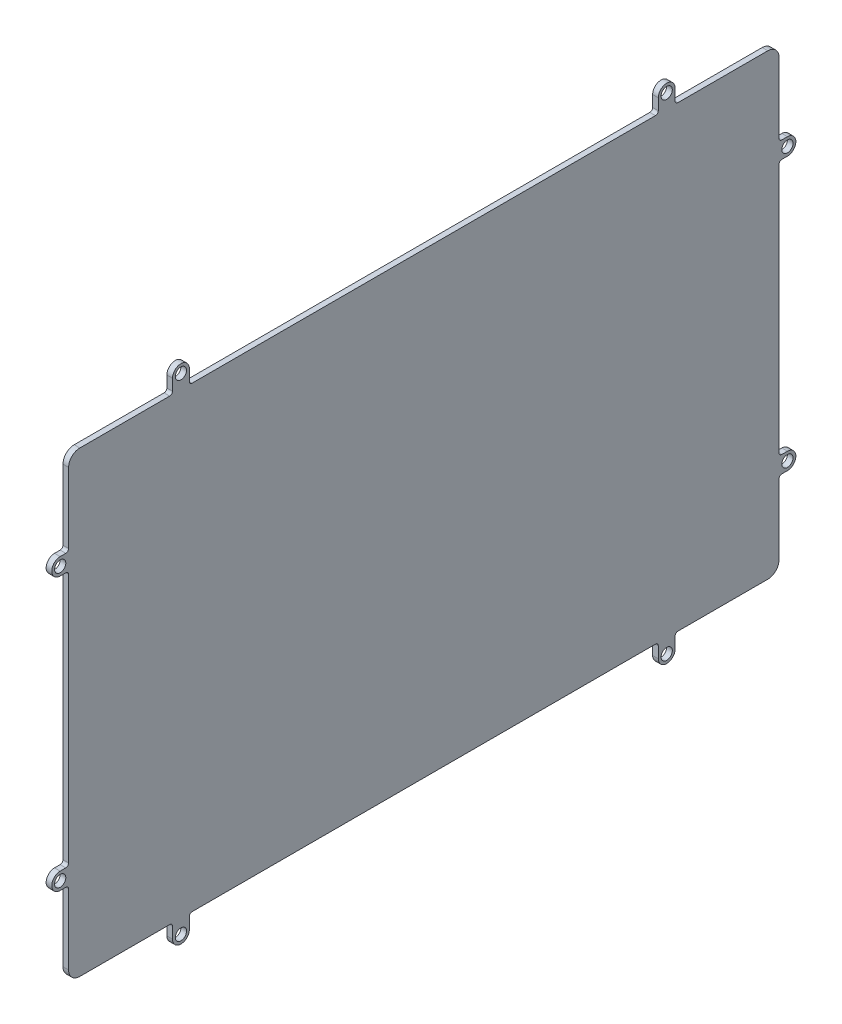
SolidWorks part; units mm, degrees
ref_plane "Ön Düzlem" through (0, 0, 0) normal (1, 0, 0) x (0, 1, 0)
ref_plane "Üst Düzlem" through (0, 0, 0) normal (0, 0, 1) x (0, 1, 0)
ref_plane "Sağ Düzlem" through (0, 0, 0) normal (0, 1, 0) x (-1, 0, 0)
sketch "Çizim1" plane through (0, 0, 0) normal (1, 0, 0) x (0, 1, 0)
  line L0 (78.6986, 126.3502) -> (53.6986, 126.3502)
  line L1 (52.6986, 127.3502) -> (52.6986, 129.3502)
  line L2 (46.6986, 129.3502) -> (46.6986, 127.3502)
  line L3 (45.6986, 126.3502) -> (-43.3014, 126.3502)
  line L4 (-44.3014, 127.3502) -> (-44.3014, 129.3502)
  line L5 (-50.3014, 129.3502) -> (-50.3014, 127.3502)
  line L6 (-51.3014, 126.3502) -> (-76.3014, 126.3502)
  line L7 (-80.3014, 122.3502) -> (-80.3014, 90.3502)
  line L8 (-81.3014, 89.3502) -> (-85.3014, 89.3502)
  line L9 (-85.3014, 83.3502) -> (-81.3014, 83.3502)
  line L10 (-80.3014, 82.3502) -> (-80.3014, -82.6498)
  line L11 (-81.3014, -83.6498) -> (-85.3014, -83.6498)
  line L12 (-85.3014, -89.6498) -> (-81.3014, -89.6498)
  line L13 (-80.3014, -90.6498) -> (-80.3014, -122.6498)
  line L14 (-76.3014, -126.6498) -> (-51.3014, -126.6498)
  line L15 (-50.3014, -127.6498) -> (-50.3014, -129.6498)
  line L16 (-44.3014, -129.6498) -> (-44.3014, -127.6498)
  line L17 (-43.3014, -126.6498) -> (45.6986, -126.6498)
  line L18 (46.6986, -127.6498) -> (46.6986, -129.6498)
  line L19 (52.6986, -129.6498) -> (52.6986, -127.6498)
  line L20 (53.6986, -126.6498) -> (78.6986, -126.6498)
  line L21 (82.6986, -122.6498) -> (82.6986, -90.6498)
  line L22 (83.6986, -89.6498) -> (87.6986, -89.6498)
  line L23 (87.6986, -83.6498) -> (83.6986, -83.6498)
  line L24 (82.6986, -82.6498) -> (82.6986, 82.3502)
  line L25 (83.6986, 83.3502) -> (87.6986, 83.3502)
  line L26 (87.6986, 89.3502) -> (83.6986, 89.3502)
  line L27 (82.6986, 90.3502) -> (82.6986, 122.3502)
  arc A0 (82.6986, 122.3502) -> (78.6986, 126.3502) centre (78.6986, 122.3502) ccw
  arc A1 (52.6986, 127.3502) -> (53.6986, 126.3502) centre (53.6986, 127.3502) ccw
  arc A2 (52.6986, 129.3502) -> (46.6986, 129.3502) centre (49.6986, 129.3502) ccw
  arc A3 (45.6986, 126.3502) -> (46.6986, 127.3502) centre (45.6986, 127.3502) ccw
  arc A4 (-44.3014, 127.3502) -> (-43.3014, 126.3502) centre (-43.3014, 127.3502) ccw
  arc A5 (-44.3014, 129.3502) -> (-50.3014, 129.3502) centre (-47.3014, 129.3502) ccw
  arc A6 (-51.3014, 126.3502) -> (-50.3014, 127.3502) centre (-51.3014, 127.3502) ccw
  arc A7 (-76.3014, 126.3502) -> (-80.3014, 122.3502) centre (-76.3014, 122.3502) ccw
  arc A8 (-81.3014, 89.3502) -> (-80.3014, 90.3502) centre (-81.3014, 90.3502) ccw
  arc A9 (-85.3014, 89.3502) -> (-85.3014, 83.3502) centre (-85.3014, 86.3502) ccw
  arc A10 (-80.3014, 82.3502) -> (-81.3014, 83.3502) centre (-81.3014, 82.3502) ccw
  arc A11 (-81.3014, -83.6498) -> (-80.3014, -82.6498) centre (-81.3014, -82.6498) ccw
  arc A12 (-85.3014, -83.6498) -> (-85.3014, -89.6498) centre (-85.3014, -86.6498) ccw
  arc A13 (-80.3014, -90.6498) -> (-81.3014, -89.6498) centre (-81.3014, -90.6498) ccw
  arc A14 (-80.3014, -122.6498) -> (-76.3014, -126.6498) centre (-76.3014, -122.6498) ccw
  arc A15 (-50.3014, -127.6498) -> (-51.3014, -126.6498) centre (-51.3014, -127.6498) ccw
  arc A16 (-50.3014, -129.6498) -> (-44.3014, -129.6498) centre (-47.3014, -129.6498) ccw
  arc A17 (-43.3014, -126.6498) -> (-44.3014, -127.6498) centre (-43.3014, -127.6498) ccw
  arc A18 (46.6986, -127.6498) -> (45.6986, -126.6498) centre (45.6986, -127.6498) ccw
  arc A19 (46.6986, -129.6498) -> (52.6986, -129.6498) centre (49.6986, -129.6498) ccw
  arc A20 (53.6986, -126.6498) -> (52.6986, -127.6498) centre (53.6986, -127.6498) ccw
  arc A21 (78.6986, -126.6498) -> (82.6986, -122.6498) centre (78.6986, -122.6498) ccw
  arc A22 (83.6986, -89.6498) -> (82.6986, -90.6498) centre (83.6986, -90.6498) ccw
  arc A23 (87.6986, -89.6498) -> (87.6986, -83.6498) centre (87.6986, -86.6498) ccw
  arc A24 (82.6986, -82.6498) -> (83.6986, -83.6498) centre (83.6986, -82.6498) ccw
  arc A25 (83.6986, 83.3502) -> (82.6986, 82.3502) centre (83.6986, 82.3502) ccw
  arc A26 (87.6986, 83.3502) -> (87.6986, 89.3502) centre (87.6986, 86.3502) ccw
  arc A27 (82.6986, 90.3502) -> (83.6986, 89.3502) centre (83.6986, 90.3502) ccw
extrude "Yükseklik-Ekstrüzyon1" add sketch "Çizim1" along normal blind 2
sketch "Çizim2" plane through (2, 0, 0) normal (1, 0, 0) x (0, 1, 0)
  circle A0 centre (-47.3014, 129.3502) radius 2
  dimension "D1" = 4
extrude "Kes-Ekstrüzyon1" cut sketch "Çizim2" against normal blind 2
sketch "Çizim3" plane through (2, 0, 0) normal (1, 0, 0) x (0, 1, 0)
  point P0 (49.6986, 129.3502)
  point P1 (87.6986, 86.3502)
  point P3 (-85.3014, 86.3502)
  point P5 (-85.3014, -86.6498)
  point P7 (-47.3014, -129.6498)
  point P9 (49.6986, -129.6498)
  point P11 (87.6986, -86.6498)
pattern_sketch "Çizim-Çoğaltma1" of "Kes-Ekstrüzyon1" driven by "Çizim3"
